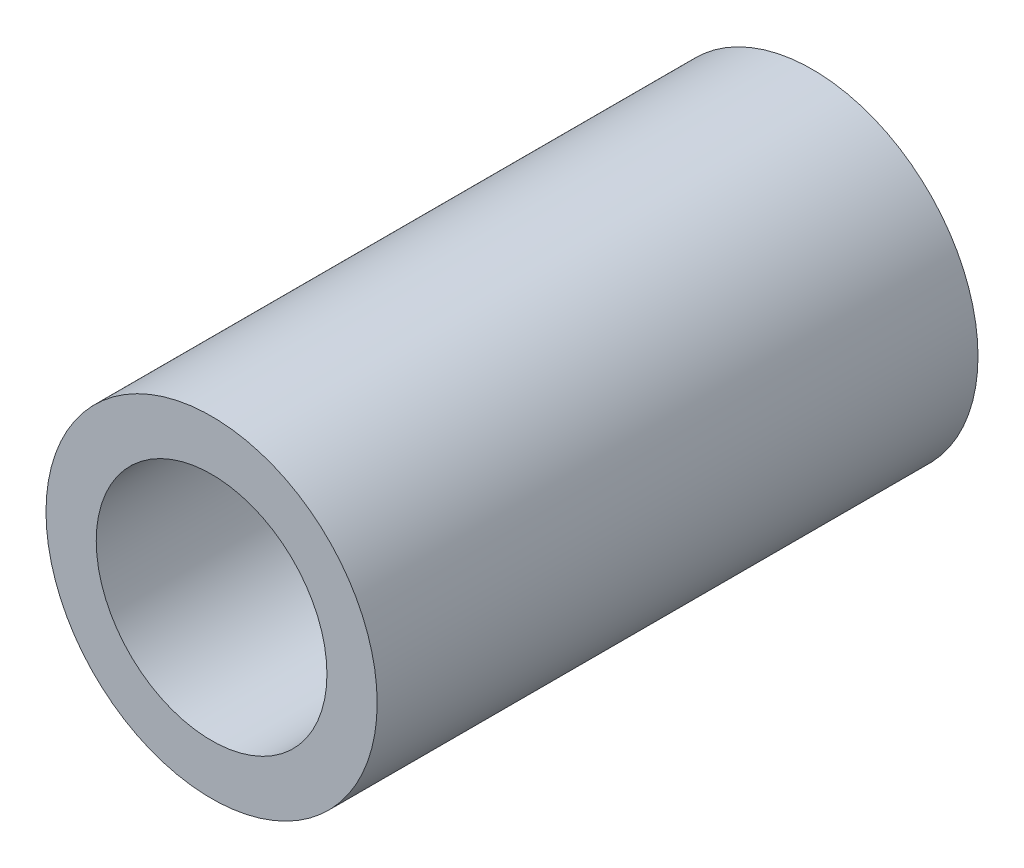
SolidWorks part; units mm, degrees
ref_plane "Front Plane" through (0, 0, 0) normal (0, 0, 1) x (1, 0, 0)
ref_plane "Top Plane" through (0, 0, 0) normal (0, 1, 0) x (1, 0, 0)
ref_plane "Right Plane" through (0, 0, 0) normal (1, 0, 0) x (0, 0, -1)
sketch "Sketch1" plane through (0, 0, 0) normal (0, 0, 1) x (1, 0, 0)
  circle A0 centre (0, 0) radius 1.75
  dimension "D1" = 3.5
extrude "Boss-Extrude1" add sketch "Sketch1" along normal blind 6.35
hole_wizard "#4 Clearance Hole1" positions "Sketch6" profile "Sketch5" hole size "#2" standard "ANSI Inch" end condition through all
sketch "Sketch6" plane through (0, 0, 0) normal (0, 0, -1) x (-1, 0, 0)
  point P0 (0, 0)
sketch "Sketch5" plane through (0, 0, 0) normal (1, 0, 0) x (0, 1, 0)
  line L0 (0, 0) -> (0, 6.35)
  line L1 (0, 6.35) -> (1.2192, 6.35)
  line L2 (1.2192, 6.35) -> (1.2192, 0)
  line L5 (1.2192, 0) -> (0, 0)
  line L11 (0, -6.35) -> (0, 107.95) construction
  dimension "Thru Hole Dia." = 2.4384
  dimension "Thru Hole Depth" = 6.35
